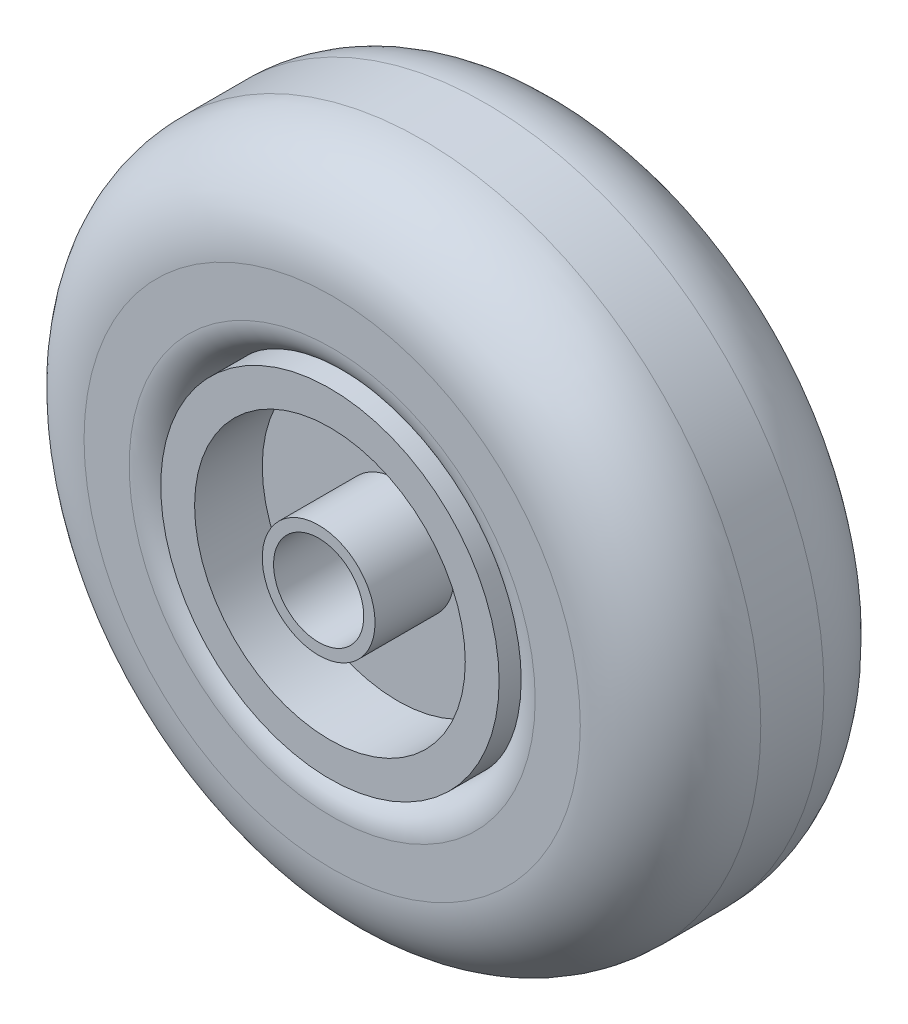
SolidWorks part; units mm, degrees
ref_plane "Front Plane" through (0, 0, 0) normal (0, 0, 1) x (1, 0, 0)
ref_plane "Top Plane" through (0, 0, 0) normal (0, 1, 0) x (1, 0, 0)
ref_plane "Right Plane" through (0, 0, 0) normal (1, 0, 0) x (0, 0, -1)
sketch "Sketch1" plane through (0, 0, 0) normal (0, 0, 1) x (1, 0, 0)
  circle A0 centre (0, 0) radius 47.625
  circle A1 centre (0, 0) radius 23.8125
  dimension "D1" = 95.25
  dimension "D2" = 47.625
extrude "Boss-Extrude1" add sketch "Sketch1" along normal mid plane 34.29
fillet "Fillet1" radius 12.7 2 edges at (47.625, 0, -17.145) (47.625, 0, 17.145)
fillet "Fillet2" radius 4.7625 2 edges at (23.8125, 0, -17.145) (23.8125, 0, 17.145)
sketch "Sketch2" plane through (0, 0, 0) normal (0, 0, 1) x (1, 0, 0)
  circle A0 centre (0, 0) radius 25.4
  dimension "D1" = 50.8
extrude "Boss-Extrude2" add sketch "Sketch2" along normal mid plane 34.925 separate body
sketch "Sketch3" plane through (0, 0, 0) normal (1, 0, 0) x (0, 0, -1)
  line L0 (0, 0) -> (130.4604, 0) construction
  line L1 (-17.4625, 25.4) -> (-17.4625, 23.8125)
  line L3 (-17.4625, 23.8125) -> (17.4625, 23.8125)
  line L4 (17.4625, 23.8125) -> (17.4625, 25.4)
  line L5 (17.4625, 25.4) -> (-17.4625, 25.4)
  line L6 (17.4625, -25.4) -> (-17.4625, -25.4)
  line L7 (-17.4625, 25.4) -> (17.4625, 25.4)
  line L8 (-17.4625, 25.4) -> (17.4625, 25.4) construction
  line L9 (17.4625, -25.4) -> (-17.4625, -25.4) construction
  line L10 (0, 23.8125) -> (0, 0) construction
  dimension "D1" = 34.925
  dimension "D2" = 47.625
revolve "Cut-Revolve1" cut sketch "Sketch3" angle 360 about L0
sketch "Sketch4" plane through (0, 0, -17.4625) normal (0, 0, -1) x (-1, 0, 0)
  circle A0 centre (0, 0) radius 19.05
  circle A1 centre (0, 0) radius 7.9375
  dimension "D1" = 15.875
  dimension "D2" = 38.1
extrude "Cut-Extrude1" cut sketch "Sketch4" against normal blind 9.525
mirror "Mirror1" about plane through (0, 0, 0) normal (0, 0, 1) of "Cut-Extrude1"
sketch "Sketch5" plane through (0, 0, 0) normal (0, 0, 1) x (1, 0, 0)
  circle A0 centre (0, 0) radius 7.9375
  circle A1 centre (0, 0) radius 7.9375 construction
extrude "Boss-Extrude3" add sketch "Sketch5" along normal mid plane 38.1
sketch "Sketch6" plane through (0, 0, -17.4625) normal (0, 0, -1) x (-1, 0, 0)
  circle A0 centre (0, 0) radius 6.35
  dimension "D1" = 12.7
extrude "Cut-Extrude2" cut sketch "Sketch6" against normal through all and the other way through all
